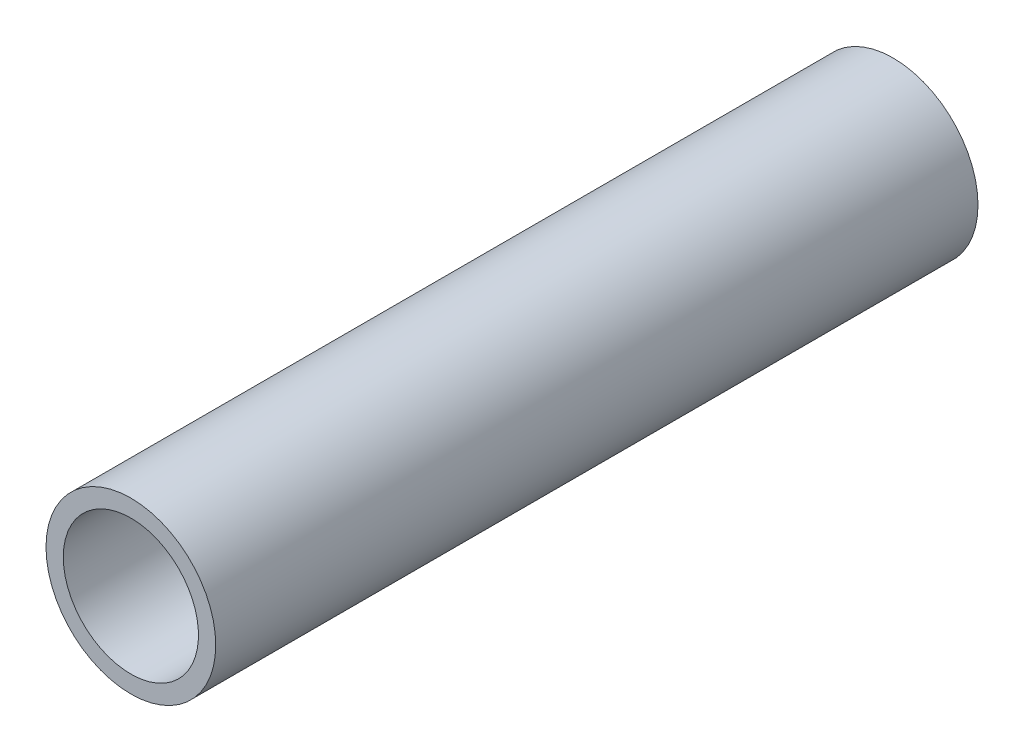
SolidWorks part; units mm, degrees
ref_plane "Front Plane" through (0, 0, 0) normal (0, 0, 1) x (1, 0, 0)
ref_plane "Top Plane" through (0, 0, 0) normal (0, 1, 0) x (1, 0, 0)
ref_plane "Right Plane" through (0, 0, 0) normal (1, 0, 0) x (0, 0, -1)
sketch "Sketch1" plane through (0, 0, 0) normal (0, 0, 1) x (1, 0, 0)
  circle A0 centre (0, 0) radius 16.7
extrude "Boss-Extrude1" add sketch "Sketch1" along normal blind 150
sketch "Sketch2" plane through (0, 0, 0) normal (0, 0, -1) x (-1, 0, 0)
  circle A0 centre (0, 0) radius 13.3
extrude "Cut-Extrude1" cut sketch "Sketch2" against normal blind 150
